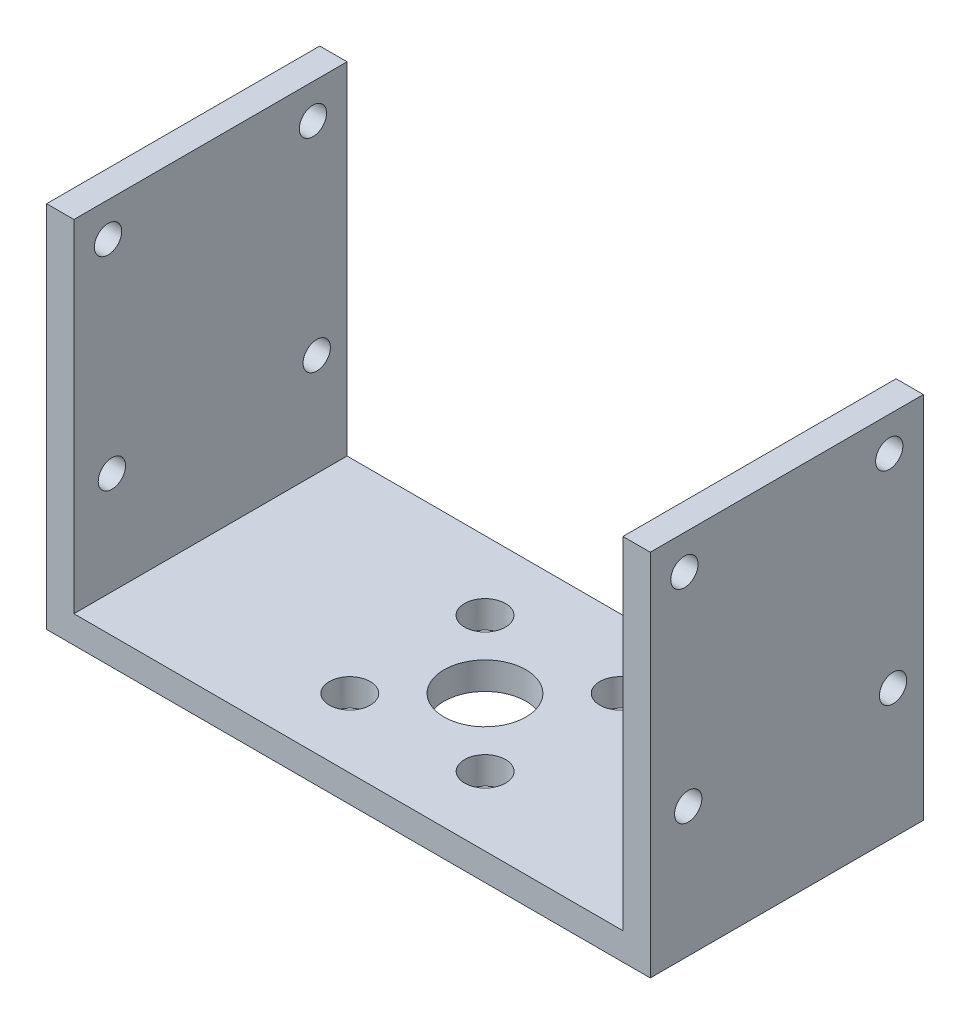
SolidWorks part; units mm, degrees
ref_plane "Front Plane" through (0, 0, 0) normal (0, 0, 1) x (1, 0, 0)
ref_plane "Top Plane" through (0, 0, 0) normal (0, 1, 0) x (1, 0, 0)
ref_plane "Right Plane" through (0, 0, 0) normal (1, 0, 0) x (0, 0, -1)
sketch "Sketch1" plane through (0, 0, 0) normal (0, 1, 0) x (1, 0, 0)
  line L1 (0, 0) -> (44.2, 0)
  line L2 (0, 0) -> (0, 20)
  line L3 (0, 20) -> (44.2, 20)
  line L4 (44.2, 0) -> (44.2, 20)
  dimension "D1" = 44.2
  dimension "D2" = 20
extrude "Boss-Extrude1" add sketch "Sketch1" along normal blind 2
sketch "Sketch2" plane through (0, 2, 0) normal (0, 1, 0) x (1, 0, 0)
  line L0 (0, 0) -> (44.2, 0) construction
  line L1 (0, 20) -> (2, 20)
  line L2 (0, 20) -> (0, 0)
  line L3 (0, 0) -> (2, 0)
  line L4 (2, 20) -> (2, 0)
  line L6 (44.2, 20) -> (42.2, 20)
  line L7 (44.2, 20) -> (44.2, 0)
  line L8 (44.2, 0) -> (42.2, 0)
  line L9 (42.2, 20) -> (42.2, 0)
  dimension "D1" = 2
  dimension "D2" = 2
extrude "Boss-Extrude2" add sketch "Sketch2" along normal blind 25
sketch "Sketch3" plane through (0, 2, 0) normal (0, 1, 0) x (1, 0, 0)
  line L0 (44.2, 0) -> (44.2, 20) construction
  line L1 (42.2, 20) -> (2, 20) construction
  circle A0 centre (22.1, 10) radius 3
  circle A1 centre (17.1505, 14.9495) radius 1.5
  circle A2 centre (17.1505, 5.0505) radius 1.5
  circle A3 centre (27.0495, 5.0595) radius 1.5
  circle A4 centre (27.0495, 14.9495) radius 1.5
  dimension "D1" = 6
  dimension "D3" = 10
  dimension "D4" = 3
  dimension "D5" = 3
  dimension "D6" = 3
  dimension "D7" = 3
  dimension "D8" = 9.899
  dimension "D2" = 22.1
  dimension "D9" = 0
  dimension "D10" = 9.89
  dimension "D11" = 0
  dimension "D12" = 9.899
  dimension "D13" = 0
  dimension "D14" = 4.9495
  dimension "D15" = 4.9495
extrude "Cut-Extrude1" cut sketch "Sketch3" against normal blind 25
sketch "Sketch5" plane through (0, 0, 0) normal (-1, 0, 0) x (0, 0, 1)
  line L0 (-20, 27) -> (0, 27) construction
  line L1 (-20, 27) -> (-20, 0) construction
  circle A0 centre (-2.5, 24.5) radius 1
  circle A1 centre (-2.7796, 9.5) radius 1
  circle A2 centre (-17.5, 24.5) radius 1
  circle A3 centre (-17.7796, 9.5) radius 1
  dimension "D1" = 2
  dimension "D2" = 2
  dimension "D3" = 2
  dimension "D4" = 2
  dimension "D5" = 2.5
  dimension "D6" = 2.5
  dimension "D7" = 15
  dimension "D8" = 2.5
  dimension "D9" = 15
  dimension "D10" = 15
  dimension "D11" = 15
extrude "Cut-Extrude2" cut sketch "Sketch5" against normal through all
